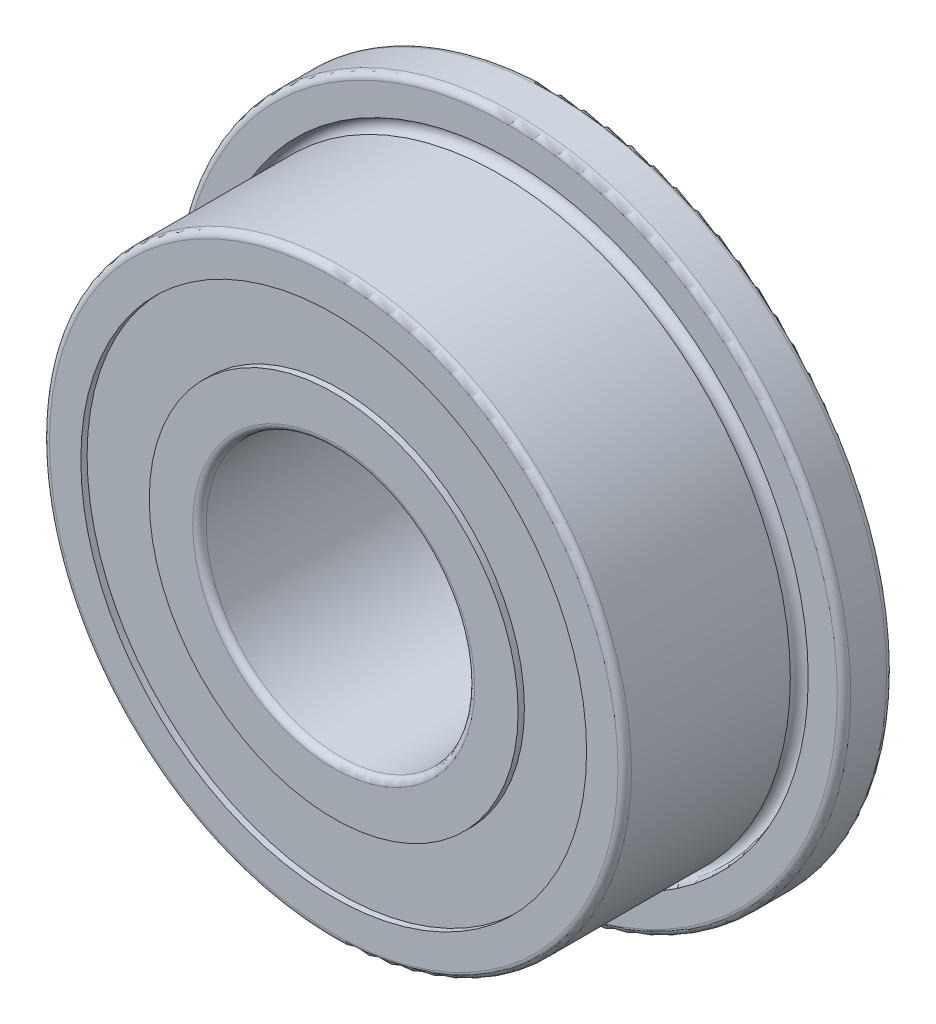
SolidWorks part; units mm, degrees
ref_plane "Plan de face" through (0, 0, 0) normal (0, 0, 1) x (1, 0, 0)
ref_plane "Plan de dessus" through (0, 0, 0) normal (0, 1, 0) x (1, 0, 0)
ref_plane "Plan de droite" through (0, 0, 0) normal (1, 0, 0) x (0, 0, -1)
ref_plane "Plan1" through (0, 0, 0) normal (1, 0, 0) x (0, 0, -1)
sketch "Esquisse1" plane through (0, 0, 0) normal (1, 0, 0) x (0, 0, -1)
  line L0 (0, 6.35) -> (0, 5.649)
  line L1 (0, 5.649) -> (0.14, 5.649)
  line L2 (0.14, 5.649) -> (0.14, 4.12)
  line L3 (0.14, 4.12) -> (0, 4.12)
  line L4 (0, 4.12) -> (0, 3.15)
  line L5 (0.15, 3) -> (4.85, 3)
  line L6 (5, 3.15) -> (5, 4.12)
  line L7 (5, 4.12) -> (4.86, 4.12)
  line L8 (4.86, 4.12) -> (4.86, 5.649)
  line L9 (4.86, 5.649) -> (5, 5.649)
  line L10 (5, 5.649) -> (5, 7.35)
  line L11 (4.85, 7.5) -> (4.05, 7.5)
  line L12 (3.9, 7.35) -> (3.9, 6.7)
  line L13 (3.7, 6.5) -> (0.15, 6.5)
  line L14 (5, 0) -> (0, 0) construction
  arc A0 (0, 3.15) -> (0.15, 3) centre (0.15, 3.15) ccw
  arc A1 (4.85, 3) -> (5, 3.15) centre (4.85, 3.15) ccw
  arc A2 (5, 7.35) -> (4.85, 7.5) centre (4.85, 7.35) ccw
  arc A3 (4.05, 7.5) -> (3.9, 7.35) centre (4.05, 7.35) ccw
  arc A4 (3.9, 6.7) -> (3.7, 6.5) centre (3.9, 6.5) cw
  arc A5 (0.15, 6.5) -> (0, 6.35) centre (0.15, 6.35) ccw
revolve "Révolution1" add sketch "Esquisse1" angle 360 about L14
